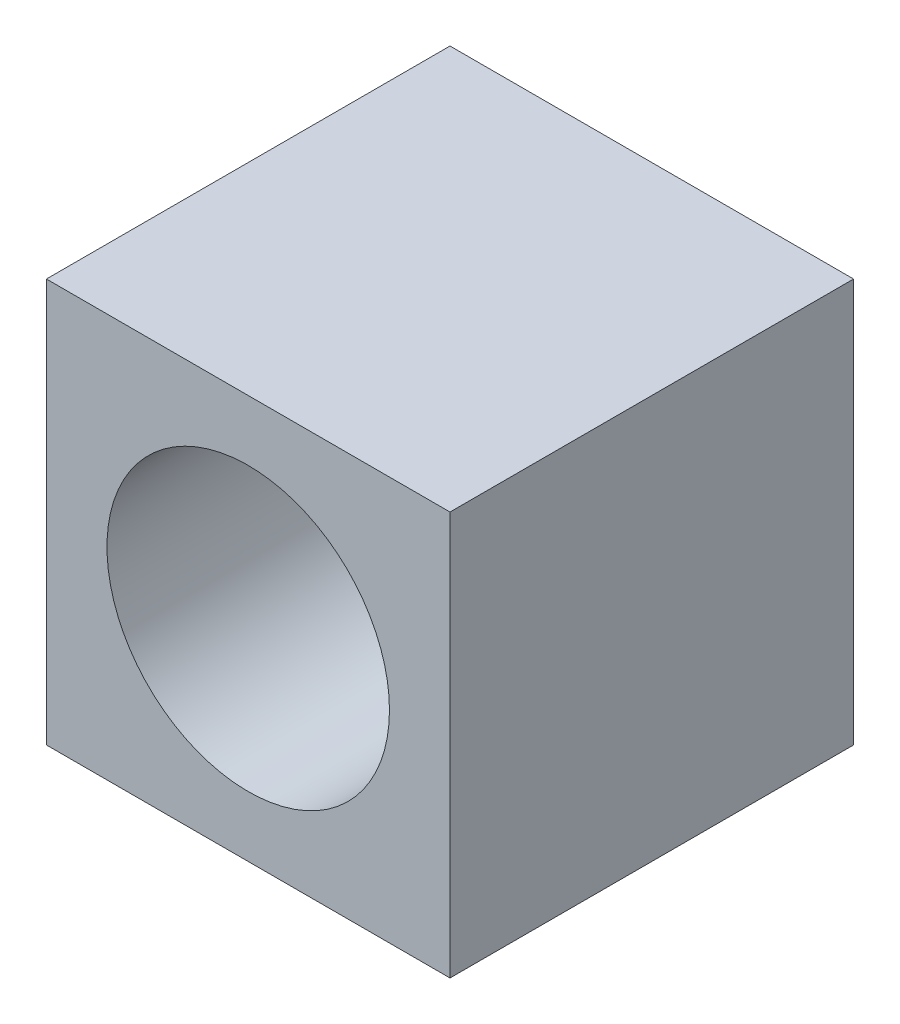
SolidWorks part; units mm, degrees
ref_plane "Alzado" through (0, 0, 0) normal (0, 0, 1) x (1, 0, 0)
ref_plane "Planta" through (0, 0, 0) normal (0, 1, 0) x (1, 0, 0)
ref_plane "Vista lateral" through (0, 0, 0) normal (1, 0, 0) x (0, 0, -1)
sketch "Sketch1" plane through (0, 0, 0) normal (0, 0, 1) x (1, 0, 0)
  line L1 (-5, -5) -> (5, -5)
  line L2 (-5, -5) -> (-5, 5)
  line L3 (-5, 5) -> (5, 5)
  line L4 (5, -5) -> (5, 5)
  point P0 (0, 0)
  dimension "D1" = 10
  dimension "D2" = 10
extrude "Boss-Extrude1" add sketch "Sketch1" along normal blind 10
sketch "Sketch2" plane through (0, 0, 10) normal (0, 0, 1) x (1, 0, 0)
  circle A0 centre (0, 0) radius 3.5
  dimension "D1" = 7
extrude "Cut-Extrude1" cut sketch "Sketch2" against normal blind 5
